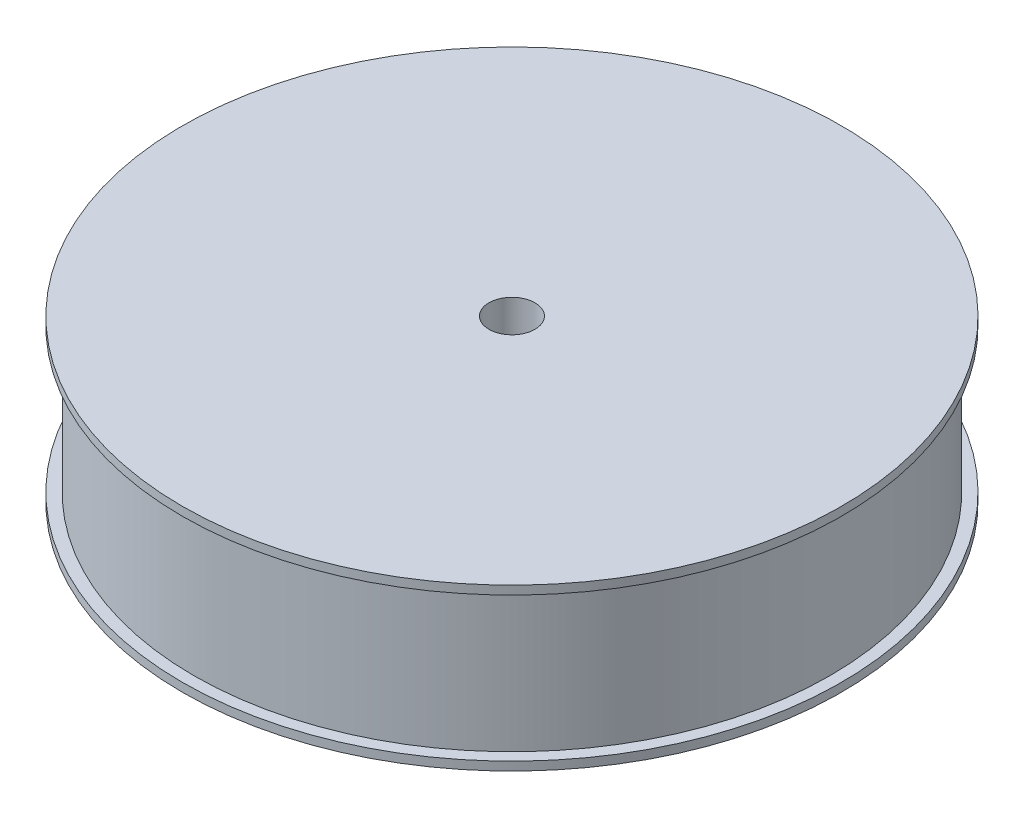
SolidWorks part; units mm, degrees
ref_plane "Front" through (0, 0, 0) normal (0, 0, 1) x (1, 0, 0)
ref_plane "Top" through (0, 0, 0) normal (0, 1, 0) x (1, 0, 0)
ref_plane "Right" through (0, 0, 0) normal (1, 0, 0) x (0, 0, -1)
sketch "Sketch1" plane through (0, 0, 0) normal (1, 0, 0) x (0, 0, -1)
  line L0 (0, 10.3155) -> (0, -12.6924) construction
  line L1 (-13.3377, 0) -> (15.1571, 0) construction
  line L2 (55.295, -12.5) -> (55.295, 12.5)
  line L3 (57.295, 12.5) -> (57.295, 14)
  line L4 (57.295, 14) -> (4, 14)
  line L5 (55.295, 12.5) -> (57.295, 12.5)
  line L6 (4, 14) -> (4, -14)
  line L7 (55.295, -12.5) -> (57.295, -12.5)
  line L8 (57.295, -12.5) -> (57.295, -14)
  line L9 (57.295, -14) -> (4, -14)
  point P11 (55.295, 0)
  point P15 (4, 0)
  dimension "D1" = 1.5
  dimension "D2" = 14
  dimension "D3" = 57.295
  dimension "D4" = 2
  dimension "D5" = 4
revolve "Revolve1" add sketch "Sketch1" angle 360 about L0
